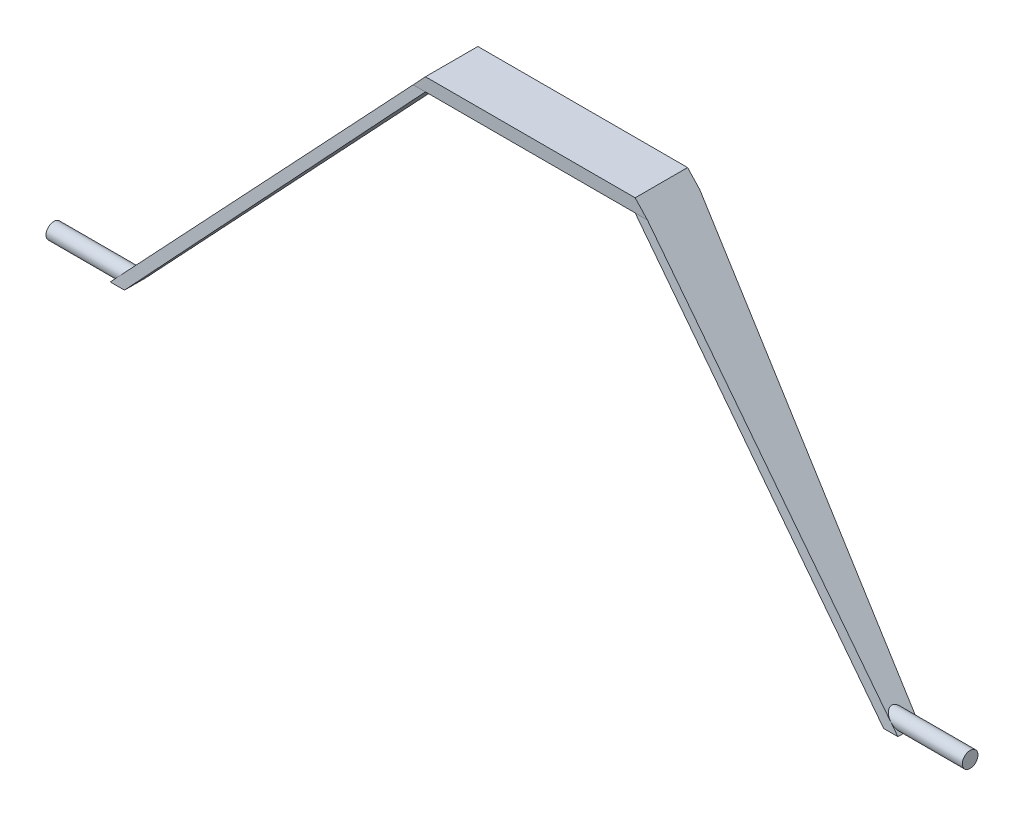
SolidWorks part; units mm, degrees
ref_plane "Front" through (0, 0, 0) normal (0, 0, 1) x (1, 0, 0)
ref_plane "Top" through (0, 0, 0) normal (0, 1, 0) x (1, 0, 0)
ref_plane "Right" through (0, 0, 0) normal (1, 0, 0) x (0, 0, -1)
sketch "Sketch12" plane through (0, 0, 0) normal (0, 0, 1) x (1, 0, 0)
  line L0 (-203.2, 241.3) -> (203.2, 241.3)
  line L1 (0, 241.3) -> (0, -425.45) construction
  line L2 (-203.2, 241.3) -> (-787.4717, -383.6692)
  line L3 (-787.4717, -383.6692) -> (-787.4717, -424.3092)
  line L4 (-787.4717, -424.3092) -> (-762.0717, -424.3092)
  line L5 (-762.0717, -424.3092) -> (-762.0717, -386.2092)
  line L6 (-762.0717, -386.2092) -> (-203.2, 215.9)
  line L7 (-203.2, 215.9) -> (203.2, 215.9)
  line L9 (762.0717, -386.2092) -> (203.2, 215.9)
  line L10 (762.0717, -424.3092) -> (762.0717, -386.2092)
  line L11 (787.4717, -424.3092) -> (762.0717, -424.3092)
  line L12 (787.4717, -383.6692) -> (787.4717, -424.3092)
  line L13 (203.2, 241.3) -> (787.4717, -383.6692)
  point P14 (0, 215.9)
  dimension "D1" = 666.75
  dimension "D2" = 40.64
  dimension "D3" = 25.4
  dimension "D4" = 38.1
extrude "Boss-Extrude6" add sketch "Sketch12" along normal blind 53.34 and the other way blind 101.6
sketch "Sketch13" plane through (787.4717, 0, 0) normal (1, 0, 0) x (0, 0, -1)
  line L0 (-53.34, -424.3092) -> (-53.34, -383.6692) construction
  line L1 (101.6, -424.3092) -> (-53.34, -424.3092) construction
  circle A0 centre (-34.29, -405.2592) radius 19.05
  dimension "D1" = 38.1
  dimension "D2" = 19.05
  dimension "D3" = 19.05
sketch "Sketch14" plane through (0, 0, 0) normal (1, 0, 0) x (0, 0, -1)
  line L0 (-53.34, 241.3) -> (0, 241.3) construction
  line L1 (101.6, 241.3) -> (-53.34, 241.3) construction
  line L2 (0, 241.3) -> (0, 215.9)
  line L5 (-53.34, -386.2092) -> (-15.24, -386.2092) construction
  line L6 (101.6, -386.2092) -> (-53.34, -386.2092) construction
  line L7 (0, 215.9) -> (-53.34, -386.2092)
  line L8 (-53.34, -386.2092) -> (-53.34, 241.3)
  line L9 (101.6, 215.9) -> (-15.24, -386.2092)
  line L10 (-15.24, -386.2092) -> (-15.24, -424.3092)
  line L11 (101.6, -424.3092) -> (-53.34, -424.3092) construction
  line L12 (-15.24, -424.3092) -> (101.6, -424.3092)
  line L13 (101.6, -424.3092) -> (101.6, 215.9)
  line L14 (-53.34, 241.3) -> (0, 241.3)
  dimension "D1" = 53.34
  dimension "D2" = 38.1
extrude "Cut-Extrude8" cut sketch "Sketch14" against normal up to surface and the other way up to surface up to face at (-495.3358, -71.1846, -24.13) other way up to face at (495.3358, -71.1846, -24.13)
ref_plane "Plane1" through (-762.0717, 0, 0) normal (-1, 0, 0) x (0, 0, 1)
sketch "Sketch15" plane through (-762.0717, 0, 0) normal (-1, 0, 0) x (0, 0, 1)
  line L0 (34.29, -405.2592) -> (34.29, -394.8452) construction
  line L1 (53.34, -386.2092) -> (53.34, -424.3092) construction
  circle A0 centre (34.29, -394.8452) radius 19.05
  dimension "D2" = 38.1
  dimension "D3" = 19.05
  dimension "D1" = 10.414
extrude "Boss-Extrude8" add sketch "Sketch15" along normal blind 127
mirror "Mirror2" about plane through (0, 0, 0) normal (1, 0, 0) of "Boss-Extrude8"
sketch "Sketch16" plane through (-762.0717, 0, 0) normal (-1, 0, 0) x (0, 0, 1)
  line L0 (15.24, -424.3092) -> (15.24, -394.8452) construction
  line L1 (15.24, -413.8952) -> (53.34, -413.8952)
  line L2 (15.24, -413.8952) -> (15.24, -424.3092)
  line L3 (15.24, -424.3092) -> (53.34, -424.3092)
  line L4 (53.34, -413.8952) -> (53.34, -424.3092)
extrude "Cut-Extrude9" cut sketch "Sketch16" along normal up to surface and the other way up to surface up to face at (-787.4717, -414.3397, 34.29) other way up to face at (787.4717, -414.3397, 34.29)
sketch "Sketch17" plane through (-762.0717, 0, 0) normal (-1, 0, 0) x (0, 0, 1)
  line L0 (34.29, -345.5692) -> (34.29, -342.5212) construction
  circle A1 centre (34.29, -342.5212) radius 15.24
  dimension "D1" = 3.048
extrude "Boss-Extrude9" add sketch "Sketch17" along normal blind 127 and the other way up to surface other way up to face at (-500.3522, -76.5504, -8.3447)
ref_plane "Plane2" through (759.5317, 0, 0) normal (-1, 0, 0) x (0, 0, 1)
sketch "Sketch18" plane through (759.5317, 0, 0) normal (-1, 0, 0) x (0, 0, 1)
  line L0 (34.1177, -345.5664) -> (34.1177, -342.5617) construction
  circle A1 centre (34.1177, -342.5617) radius 15.24
  dimension "D1" = 30.48
extrude "Boss-Extrude10" add sketch "Sketch18" against normal blind 127 and the other way up to surface other way up to face at (500.3522, -76.5504, -8.3447)
sketch "Sketch19" plane through (759.5317, 0, 0) normal (-1, 0, 0) x (0, 0, 1)
  line L0 (53.34, -413.8952) -> (53.34, -360.8092)
  line L8 (10.3111, -413.8952) -> (53.34, -413.8952)
  line L9 (53.34, -360.8092) -> (53.34, -357.7612)
  line L10 (53.34, -357.7612) -> (9.7196, -357.7612)
  line L11 (-101.6, 215.9) -> (14.7471, -383.6692) construction
  line L12 (9.7196, -357.7612) -> (9.7196, -413.8952)
  line L13 (9.7196, -413.8952) -> (10.3111, -413.8952)
extrude "Cut-Extrude10" cut sketch "Sketch19" against normal up to surface and the other way up to surface up to face at (889.0717, -394.8452, 53.34) other way up to face at (-889.0717, -394.8452, 53.34)
